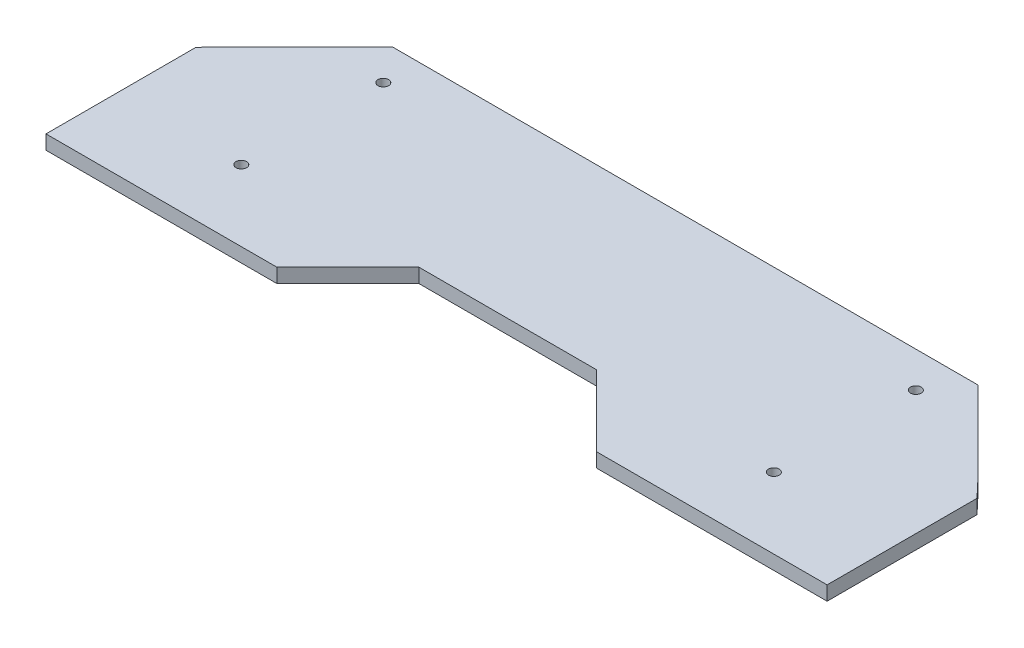
SolidWorks part; units mm, degrees
ref_plane "前视基准面" through (0, 0, 0) normal (0, 0, 1) x (1, 0, 0)
ref_plane "上视基准面" through (0, 0, 0) normal (0, 1, 0) x (1, 0, 0)
ref_plane "右视基准面" through (0, 0, 0) normal (1, 0, 0) x (0, 0, -1)
sketch "草图1" plane through (0, 0, 0) normal (0, 1, 0) x (1, 0, 0)
  line L0 (-67.5, -35) -> (-47.5, -15)
  line L1 (-137.5, -35) -> (-67.5, -35)
  line L2 (-137.5, -35) -> (-137.5, 15)
  line L3 (-117.5, 35) -> (72.5, 35)
  line L4 (92.5, -35) -> (92.5, 15)
  line L5 (22.5, -35) -> (92.5, -35)
  line L6 (-137.5, 15) -> (-117.5, 35)
  line L7 (-22.5, 61.4781) -> (-22.5, -135.1347) construction
  line L8 (92.5, 15) -> (72.5, 35)
  line L9 (-47.5, -15) -> (2.5, -15)
  line L13 (22.5, -35) -> (2.5, -15)
  point P0 (0, 0)
  point P6 (0, -35)
  dimension "D1" = 230
  dimension "D3" = 50
  dimension "D4" = 20
  dimension "D5" = 70
  dimension "D6" = 70
  dimension "D7" = 135
  dimension "D8" = 20
extrude "凸台-拉伸1" add sketch "草图1" along normal blind 4
sketch "草图2" plane through (0, 4, 0) normal (0, 1, 0) x (1, 0, 0)
  line L0 (-137.5, -35) -> (-67.5, -35) construction
  line L1 (-47.5, -15) -> (2.5, -15) construction
  line L2 (-22.5, 54.05) -> (-22.5, -68.4645) construction
  circle A0 centre (-97.5, -15) radius 1.5
  circle A1 centre (-97.5, 25) radius 1.5
  circle A2 centre (52.5, 25) radius 1.5
  circle A3 centre (52.5, -15) radius 1.5
  point P8 (-22.5, -15)
  dimension "D1" = 40
  dimension "D2" = 20
  dimension "D3" = 75
extrude "切除-拉伸1" cut sketch "草图2" against normal blind 4
sketch "草图3" plane through (0, 4, 0) normal (0, 1, 0) x (1, 0, 0)
  line L1 (-137.5, -35) -> (-127.5, -35)
  line L2 (-137.5, -35) -> (-137.5, 34.6789)
  line L3 (-137.5, 34.6789) -> (-127.5, 34.6789)
  line L4 (-127.5, -35) -> (-127.5, 34.6789)
  line L5 (92.5, -35) -> (82.5, -35)
  line L6 (92.5, -35) -> (92.5, 58.0477)
  line L7 (92.5, 58.0477) -> (82.5, 58.0477)
  line L8 (82.5, -35) -> (82.5, 58.0477)
  dimension "D1" = 10
  dimension "D2" = 10
extrude "切除-拉伸2" cut sketch "草图3" against normal blind 4
sketch "草图4" plane through (0, 4, 0) normal (0, 1, 0) x (1, 0, 0)
  line L0 (-127.5, 12.5) -> (-92.1971, 47.8029)
  line L1 (-127.5, -35) -> (-127.5, 25) construction
  line L2 (-92.1971, 47.8029) -> (-150.179, 47.8029)
  line L3 (-150.179, 47.8029) -> (-127.5, 12.5)
  line L4 (82.5, 12.5) -> (37.0053, 57.9947)
  line L5 (82.5, 25) -> (82.5, -35) construction
  line L6 (37.0053, 57.9947) -> (96.5441, 56.2052)
  line L7 (96.5441, 56.2052) -> (82.5, 12.5)
  line L8 (-127.5, -35) -> (-67.5, -35) construction
  line L9 (22.5, -35) -> (82.5, -35) construction
  dimension "D1" = 47.5
  dimension "D2" = 47.5
extrude "切除-拉伸3" cut sketch "草图4" against normal blind 4
sketch "草图5" plane through (0, 4, 0) normal (0, 1, 0) x (1, 0, 0)
  line L0 (-127.5, 12.5) -> (-132.5, 7.2156)
  line L1 (-132.5, 7.2156) -> (-132.5, -35)
  line L2 (-132.5, -35) -> (-127.5, -35)
  line L3 (-127.5, -35) -> (-127.5, 12.5)
  line L4 (-22.5, 57.3587) -> (-22.5, -45.29) construction
  line L5 (82.5, -35) -> (82.5, 12.5)
  line L6 (87.5, -35) -> (82.5, -35)
  line L7 (87.5, 7.2156) -> (87.5, -35)
  line L8 (82.5, 12.5) -> (87.5, 7.2156)
  dimension "D1" = 5
extrude "凸台-拉伸2" add sketch "草图5" against normal up to surface (4 mm away) up to face at (-22.5, 0, 7.5)
